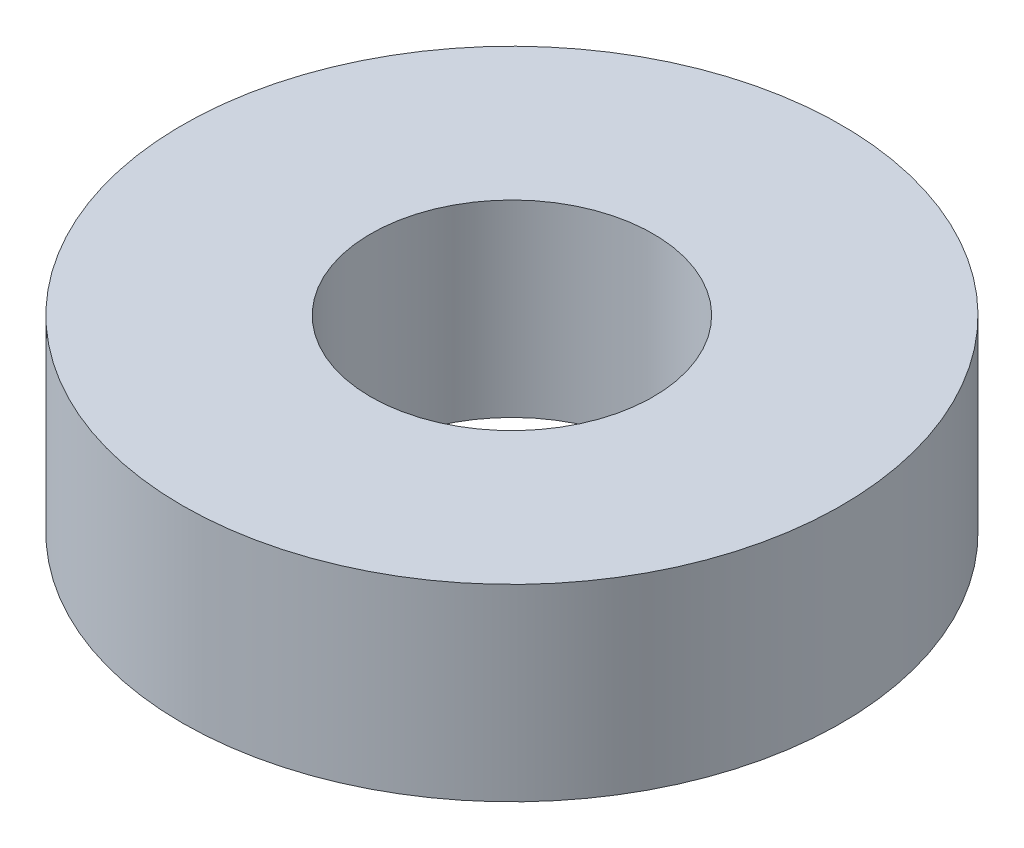
SolidWorks part; units mm, degrees
material "不锈钢 (铁素体)"
ref_plane "前视基准面" through (0, 0, 0) normal (0, 0, 1) x (1, 0, 0)
ref_plane "上视基准面" through (0, 0, 0) normal (0, 1, 0) x (1, 0, 0)
ref_plane "右视基准面" through (0, 0, 0) normal (1, 0, 0) x (0, 0, -1)
sketch "草图1" plane through (0, 0, 0) normal (0, 1, 0) x (1, 0, 0)
  circle A0 centre (0, 0) radius 1.5
  circle A1 centre (0, 0) radius 3.5
  dimension "D1" = 3
  dimension "D2" = 7
extrude "凸台-拉伸1" add sketch "草图1" along normal blind 2
